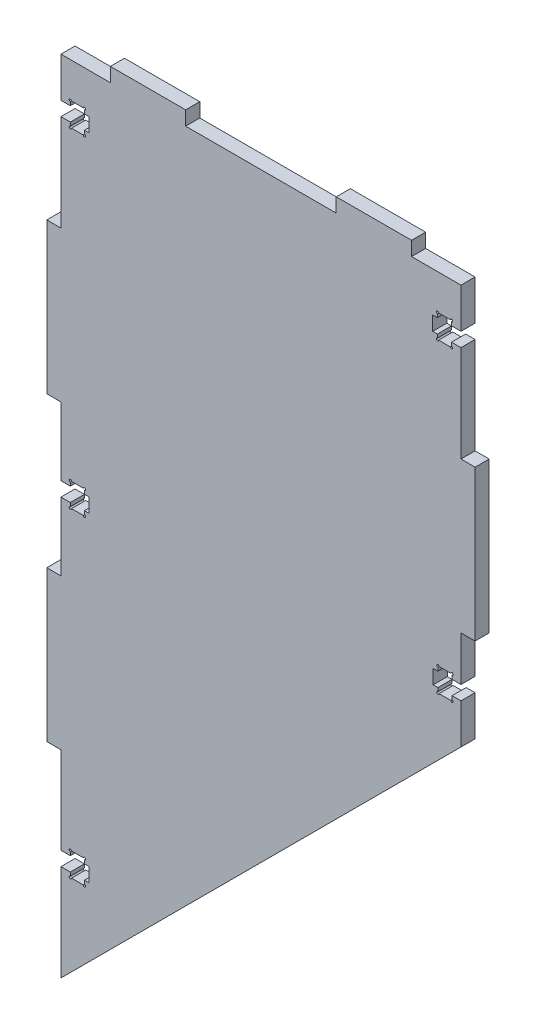
SolidWorks part; units mm, degrees
ref_plane "Front" through (0, 0, 0) normal (0, 0, 1) x (1, 0, 0)
ref_plane "Top" through (0, 0, 0) normal (0, 1, 0) x (1, 0, 0)
ref_plane "Right" through (0, 0, 0) normal (1, 0, 0) x (0, 0, -1)
sketch "Croquis1" plane through (0, 0, 0) normal (0, 0, 1) x (1, 0, 0)
  line L0 (0, 0) -> (0, 42)
  line L1 (0, 170) -> (85, 170)
  line L2 (85, 170) -> (85, 138)
  line L3 (85, 85) -> (0, 0)
  line L4 (0, 138) -> (-3, 138)
  line L5 (-3, 138) -> (-3, 106)
  line L6 (-3, 106) -> (0, 106)
  line L7 (0, 74) -> (-3, 74)
  line L8 (-3, 74) -> (-3, 42)
  line L9 (-3, 42) -> (0, 42)
  line L10 (0, 138) -> (0, 170)
  line L11 (0, 74) -> (0, 106)
  line L12 (85, 138) -> (88, 138)
  line L13 (88, 138) -> (88, 106)
  line L14 (88, 106) -> (85, 106)
  line L15 (85, 106) -> (85, 85)
  line L16 (42.5, 170) -> (42.5, 138) construction
  line L17 (26.5, 170) -> (10.5, 170)
  line L18 (26.5, 170) -> (26.5, 173)
  line L19 (26.5, 173) -> (10.5, 173)
  line L20 (10.5, 170) -> (10.5, 173)
  line L21 (26.5, 170) -> (10.5, 173) construction
  line L22 (26.5, 173) -> (10.5, 170) construction
  line L23 (58.5, 173) -> (74.5, 170) construction
  line L24 (58.5, 170) -> (74.5, 173) construction
  line L25 (74.5, 170) -> (74.5, 173)
  line L26 (58.5, 173) -> (74.5, 173)
  line L27 (58.5, 170) -> (58.5, 173)
  line L28 (58.5, 170) -> (74.5, 170)
  point P21 (18.5, 171.5)
  point P28 (66.5, 171.5)
  dimension "D1" = 85
  dimension "D2" = 170
  dimension "D3" = 85
  dimension "D4" = 3
  dimension "D5" = 32
  dimension "D6" = 32
  dimension "D8" = 32
  dimension "D9" = 32
  dimension "D10" = 3
  dimension "D11" = 16
  dimension "D12" = 16
  dimension "D13" = 3
  dimension "D7" = 2
extrude "Saliente-Extruir1" add sketch "Croquis1" along normal blind 3 contours L15 L14 L13 L12 L2 L1 L10 L4 L5 L6 L11 L7 L8 L9 L0 L3 | L27 L1 L25 L26 | L20 L1 L18 L19
sketch "Croquis2" plane through (0, 0, 3) normal (0, 0, 1) x (1, 0, 0)
  line L0 (0, 161.5) -> (2, 161.5)
  line L1 (0, 138) -> (0, 170) construction
  line L2 (2, 161.5) -> (2, 162.25)
  line L3 (2.25, 162.5) -> (4.75, 162.5)
  line L4 (5, 162.25) -> (5, 161.5)
  line L5 (5, 161.5) -> (6, 161.5)
  line L6 (6, 161.5) -> (6, 158.5)
  line L7 (5.9001, 160) -> (0, 160) construction
  line L8 (5, 158.5) -> (6, 158.5)
  line L9 (5, 157.75) -> (5, 158.5)
  line L10 (2.25, 157.5) -> (4.75, 157.5)
  line L11 (2, 158.5) -> (2, 157.75)
  line L12 (0, 158.5) -> (2, 158.5)
  line L13 (0, 90) -> (12.4066, 90) construction
  line L14 (0, 74) -> (0, 106) construction
  line L15 (0, 91.5) -> (2, 91.5)
  line L16 (2, 91.5) -> (2, 92.25)
  line L17 (2.25, 92.5) -> (4.75, 92.5)
  line L18 (5, 92.25) -> (5, 91.5)
  line L19 (5, 91.5) -> (6, 91.5)
  line L20 (6, 91.5) -> (6, 88.5)
  line L21 (5.9001, 90) -> (0, 90) construction
  line L22 (5, 88.5) -> (6, 88.5)
  line L23 (5, 87.75) -> (5, 88.5)
  line L24 (2.25, 87.5) -> (4.75, 87.5)
  line L25 (2, 88.5) -> (2, 87.75)
  line L26 (0, 88.5) -> (2, 88.5)
  line L27 (0, 42) -> (0, 22) construction
  line L28 (0, 0) -> (0, 42) construction
  line L29 (0, 23.5) -> (2, 23.5)
  line L30 (2, 23.5) -> (2, 24.25)
  line L31 (2.25, 24.5) -> (4.75, 24.5)
  line L32 (5, 24.25) -> (5, 23.5)
  line L33 (5, 23.5) -> (6, 23.5)
  line L34 (6, 23.5) -> (6, 20.5)
  line L35 (5.9001, 22) -> (0, 22) construction
  line L36 (5, 20.5) -> (6, 20.5)
  line L37 (5, 19.75) -> (5, 20.5)
  line L38 (2.25, 19.5) -> (4.75, 19.5)
  line L39 (2, 20.5) -> (2, 19.75)
  line L40 (0, 20.5) -> (2, 20.5)
  line L41 (42.5, 170) -> (42.5, 98.528) construction
  line L42 (26.5, 170) -> (58.5, 170) construction
  line L43 (79.0999, 95) -> (85, 95) construction
  line L44 (79.0999, 160) -> (85, 160) construction
  line L45 (85.0999, 93.5) -> (83.0999, 93.5)
  line L46 (83.0999, 93.5) -> (83.0999, 92.75)
  line L47 (82.8499, 92.5) -> (80.3499, 92.5)
  line L48 (80.0999, 92.75) -> (80.0999, 93.5)
  line L49 (80.0999, 93.5) -> (79.0999, 93.5)
  line L50 (79.0999, 96.5) -> (79.0999, 93.5)
  line L51 (80.0999, 96.5) -> (79.0999, 96.5)
  line L52 (80.0999, 97.25) -> (80.0999, 96.5)
  line L53 (82.8499, 97.5) -> (80.3499, 97.5)
  line L54 (83.0999, 96.5) -> (83.0999, 97.25)
  line L55 (85.0999, 96.5) -> (83.0999, 96.5)
  line L56 (85, 158.5) -> (83, 158.5)
  line L57 (83, 158.5) -> (83, 157.75)
  line L58 (82.75, 157.5) -> (80.25, 157.5)
  line L59 (80, 157.75) -> (80, 158.5)
  line L60 (80, 158.5) -> (79, 158.5)
  line L61 (79, 161.5) -> (79, 158.5)
  line L62 (80, 161.5) -> (79, 161.5)
  line L63 (80, 162.25) -> (80, 161.5)
  line L64 (82.75, 162.5) -> (80.25, 162.5)
  line L65 (83, 161.5) -> (83, 162.25)
  line L66 (85, 161.5) -> (83, 161.5)
  arc A0 (5, 162.25) -> (4.75, 162.5) centre (5, 162.5) ccw
  arc A1 (2.25, 162.5) -> (2, 162.25) centre (2, 162.5) ccw
  arc A2 (2.25, 157.5) -> (2, 157.75) centre (2, 157.5) cw
  arc A3 (5, 157.75) -> (4.75, 157.5) centre (5, 157.5) cw
  arc A4 (5, 92.25) -> (4.75, 92.5) centre (5, 92.5) ccw
  arc A5 (2.25, 92.5) -> (2, 92.25) centre (2, 92.5) ccw
  arc A6 (2.25, 87.5) -> (2, 87.75) centre (2, 87.5) cw
  arc A7 (5, 87.75) -> (4.75, 87.5) centre (5, 87.5) cw
  arc A8 (5, 24.25) -> (4.75, 24.5) centre (5, 24.5) ccw
  arc A9 (2.25, 24.5) -> (2, 24.25) centre (2, 24.5) ccw
  arc A10 (2.25, 19.5) -> (2, 19.75) centre (2, 19.5) cw
  arc A11 (5, 19.75) -> (4.75, 19.5) centre (5, 19.5) cw
  arc A12 (80.0999, 92.75) -> (80.3499, 92.5) centre (80.0999, 92.5) ccw
  arc A13 (82.8499, 92.5) -> (83.0999, 92.75) centre (83.0999, 92.5) ccw
  arc A14 (82.8499, 97.5) -> (83.0999, 97.25) centre (83.0999, 97.5) cw
  arc A15 (80.0999, 97.25) -> (80.3499, 97.5) centre (80.0999, 97.5) cw
  arc A16 (80, 157.75) -> (80.25, 157.5) centre (80, 157.5) ccw
  arc A17 (82.75, 157.5) -> (83, 157.75) centre (83, 157.5) ccw
  arc A18 (82.75, 162.5) -> (83, 162.25) centre (83, 162.5) cw
  arc A19 (80, 162.25) -> (80.25, 162.5) centre (80, 162.5) cw
  point P5 (6, 160)
  point P33 (6, 90)
  point P61 (6, 22)
  point P129 (79.0999, 95)
  point P130 (79, 160)
  line M10 (85, 85) -> (85, 106)
  line M14 (85, 138) -> (85, 170)
  line M24 (0, 170) -> (0, 138)
  line M28 (0, 106) -> (0, 74)
  line M32 (0, 42) -> (0, 0)
  dimension "D1" = 3
  dimension "D2" = 1
  dimension "D6" = 0.5
  dimension "D7" = 0.5
  dimension "D12" = 0.5
  dimension "D13" = 0.5
  dimension "D20" = 0.5
  dimension "D21" = 0.5
  dimension "D30" = 0.25
  dimension "D31" = 0.25
  dimension "D32" = 0.25
  dimension "D33" = 0.25
  dimension "D3" = 2
  dimension "D4" = 1.5
  dimension "D5" = 2.5
  dimension "D8" = 10
  dimension "D9" = 2
  dimension "D10" = 1.5
  dimension "D11" = 2.5
  dimension "D14" = 3
  dimension "D15" = 1
  dimension "D16" = 20
  dimension "D17" = 2
  dimension "D18" = 1.5
  dimension "D19" = 2.5
  dimension "D22" = 3
  dimension "D23" = 1
  dimension "D24" = 65
  dimension "D25" = 3
  dimension "D26" = 1.5
  dimension "D27" = 3
  dimension "D28" = 2.5
  dimension "D29" = 2
  dimension "D34" = 1.5
extrude "Cortar-Extruir1" cut sketch "Croquis2" against normal through all contours A7 L23 L22 L20 L19 L18 A4 L17 A5 L16 L15 L26 L25 A6 L24 M28 | A3 L9 L8 L6 L5 L4 A0 L3 A1 L2 L0 L12 L11 A2 L10 M24 | A19 L63 L62 L61 L60 L59 A16 L58 A17 L57 L56 L66 L65 A18 L64 M14 | A11 L37 L36 L34 L33 L32 A8 L31 A9 L30 L29 L40 L39 A10 L38 M32 | A15 L52 L51 L50 L49 L48 A12 L47 A13 L46 L45 L55 L54 A14 L53 M10
